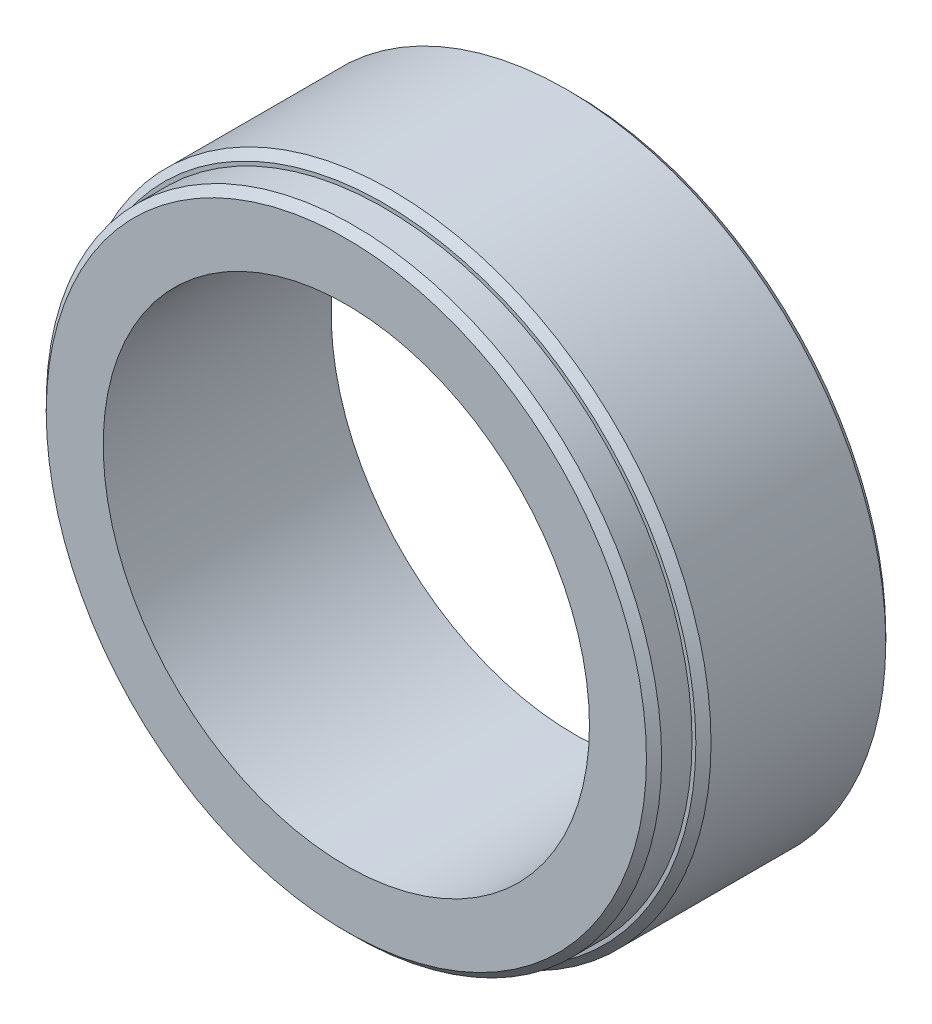
SolidWorks part; units mm, degrees
ref_plane "Front Plane" through (0, 0, 0) normal (0, 0, 1) x (1, 0, 0)
ref_plane "Top Plane" through (0, 0, 0) normal (0, 1, 0) x (1, 0, 0)
ref_plane "Right Plane" through (0, 0, 0) normal (1, 0, 0) x (0, 0, -1)
sketch "Sketch1" plane through (0, 0, 0) normal (0, 0, 1) x (1, 0, 0)
  circle A0 centre (0, 0) radius 32
  circle A1 centre (0, 0) radius 42
  dimension "D1" = 64
  dimension "D2" = 84
extrude "Boss-Extrude1" add sketch "Sketch1" along normal blind 25
sketch "Sketch2" plane through (0, 0, 25) normal (0, 0, 1) x (1, 0, 0)
  circle A0 centre (0, 0) radius 40.5
  circle A1 centre (0, 0) radius 32 construction
  circle A2 centre (0, 0) radius 32
  dimension "D1" = 81
extrude "Boss-Extrude2" add sketch "Sketch2" along normal blind 5
chamfer "Chamfer1" distance 1 angle 45 3 edges at (42, 0, 0) (42, 0, 25) (40.5, 0, 30)
